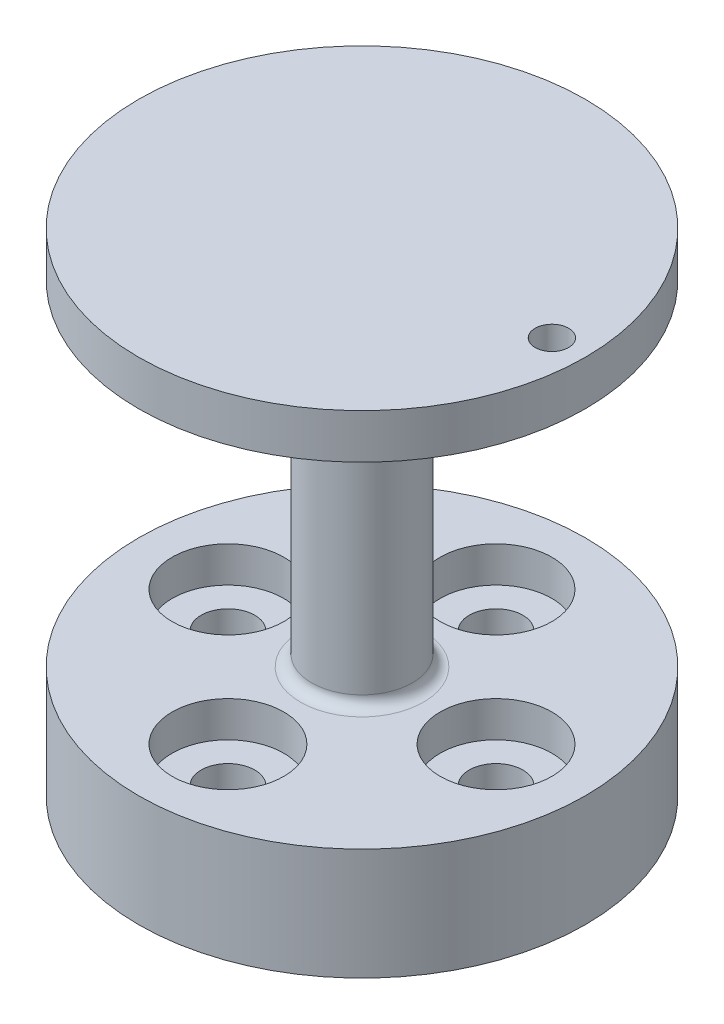
SolidWorks part; units mm, degrees
ref_plane "Front Plane" through (0, 0, 0) normal (0, 0, 1) x (1, 0, 0)
ref_plane "Top Plane" through (0, 0, 0) normal (0, 1, 0) x (1, 0, 0)
ref_plane "Right Plane" through (0, 0, 0) normal (1, 0, 0) x (0, 0, -1)
sketch "Sketch1" plane through (0, 0, 0) normal (0, 1, 0) x (1, 0, 0)
  circle A0 centre (0, 0) radius 10
  dimension "D1" = 20
extrude "bottom" add sketch "Sketch1" along normal blind 5
sketch "Sketch2" plane through (0, 5, 0) normal (0, 1, 0) x (1, 0, 0)
  circle A0 centre (6, 0) radius 1.2
  point P0 (6, 0)
  dimension "D1" = 2.4
  dimension "D2" = 6
hole_wizard "CBORE for M2 Pan Head Screw1" positions "Sketch2" profile "Sketch3" counterbore size "M2" standard "DIN" end condition through all
sketch "Sketch3" plane through (6, 5, 0) normal (1, 0, 0) x (0, 0, 1)
  line L0 (0, 0) -> (0, 5)
  line L1 (0, 5) -> (1.2, 5)
  line L3 (1.2, 5) -> (1.2, 1.6)
  line L4 (1.2, 1.6) -> (2.5, 1.6)
  line L5 (2.5, 1.6) -> (2.5, 0)
  line L7 (2.5, 0) -> (0, 0)
  line L11 (0, -6.35) -> (0, 107.95) construction
  dimension "Thru Hole Dia." = 2.4
  dimension "Thru Hole Depth" = 5
  dimension "C'Bore Dia." = 5
  dimension "C'Bore Depth" = 1.6
sketch "Sketch4" plane through (0, 5, 0) normal (0, 1, 0) x (1, 0, 0)
  circle A0 centre (0, 0) radius 2.25
  dimension "D1" = 4.5
extrude "groove" add sketch "Sketch4" along normal blind 15
pattern_circular "CirPattern1" count 4 over 360 about axis through (0, 0, 0) along (0, 1, 0) of "CBORE for M2 Pan Head Screw1"
fillet "Fillet1" radius 0.5 1 edges at (0, 5, 2.25)
sketch "Sketch7" plane through (0, 20, 0) normal (0, 1, 0) x (1, 0, 0)
  circle A0 centre (0, 0) radius 10 construction
  circle A1 centre (0, 0) radius 10
extrude "top" add sketch "Sketch7" along normal blind 2
sketch "Sketch8" plane through (0, 22, 0) normal (0, 1, 0) x (1, 0, 0)
  circle A0 centre (8.5, 0) radius 0.75
  circle A1 centre (0, 0) radius 10 construction
  point P4 (0, 0)
  dimension "D1" = 1.5
  dimension "D2" = 8.5
extrude "thread_terminal" cut sketch "Sketch8" against normal up to surface (2 mm away) up to face at (0, 20, 2.25)
fillet "Fillet2" radius 5 1 edges at (0, 20, 2.25)
